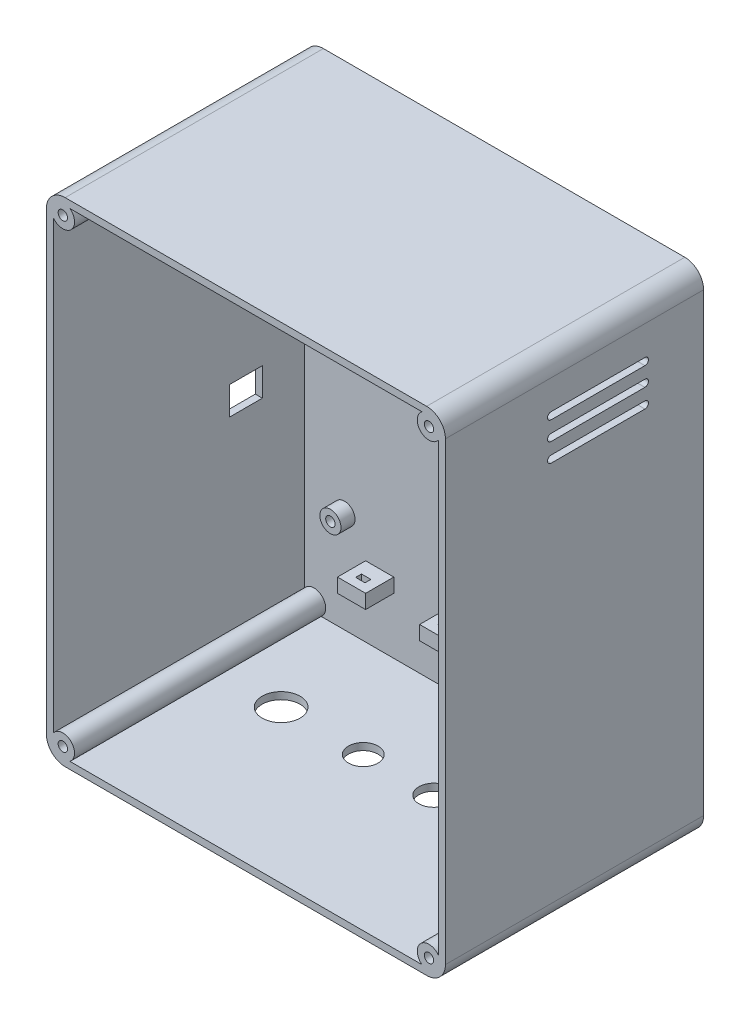
SolidWorks part; units mm, degrees
ref_plane "Front Plane" through (0, 0, 0) normal (0, 0, 1) x (1, 0, 0)
ref_plane "Top Plane" through (0, 0, 0) normal (0, 1, 0) x (1, 0, 0)
ref_plane "Right Plane" through (0, 0, 0) normal (1, 0, 0) x (0, 0, -1)
sketch "Sketch1" plane through (0, 0, 0) normal (0, 0, 1) x (1, 0, 0)
  line L0 (-77, 0) -> (77, 0)
  line L1 (85, 8) -> (85, 202)
  line L2 (77, 210) -> (-77, 210)
  line L3 (-85, 202) -> (-85, 8)
  arc A0 (-85, 8) -> (-77, 0) centre (-77, 8) ccw
  arc A1 (77, 0) -> (85, 8) centre (77, 8) ccw
  arc A2 (85, 202) -> (77, 210) centre (77, 202) ccw
  arc A3 (-77, 210) -> (-85, 202) centre (-77, 202) ccw
extrude "Block" add sketch "Sketch1" along normal blind 110
shell "Shell1" thickness 3
sketch "Sketch2" plane through (0, 0, 0) normal (0, 0, 1) x (1, 0, 0)
  circle A0 centre (-78, 7) radius 5
  circle A1 centre (78, 7) radius 5
  circle A2 centre (-78, 203) radius 5
  circle A3 centre (78, 203) radius 5
extrude "Corner columns" add sketch "Sketch2" along normal blind 110
ref_plane "P1_Front_110" through (0, 0, 110) normal (0, 0, 1) x (1, 0, 0)
sketch "Sketch3" plane through (0, 0, 110) normal (0, 0, 1) x (1, 0, 0)
  circle A0 centre (-78, 7) radius 2
  circle A1 centre (78, 7) radius 2
  circle A2 centre (-78, 203) radius 2
  circle A3 centre (78, 203) radius 2
extrude "Front panel insert holes" cut sketch "Sketch3" against normal blind 7
ref_plane "P2_Front_3" through (0, 0, 3) normal (0, 0, 1) x (1, 0, 0)
sketch "Sketch4" plane through (0, 0, 3) normal (0, 0, 1) x (1, 0, 0)
  circle A0 centre (-65, 46) radius 4.5
  circle A1 centre (65, 46) radius 4.5
  circle A2 centre (-65, 190) radius 4.5
  circle A3 centre (65, 190) radius 4.5
extrude "Plate bosses" add sketch "Sketch4" along normal blind 6
ref_plane "P3_Front_9" through (0, 0, 9) normal (0, 0, 1) x (1, 0, 0)
sketch "Sketch5" plane through (0, 0, 9) normal (0, 0, 1) x (1, 0, 0)
  circle A0 centre (-65, 46) radius 2
  circle A1 centre (65, 46) radius 2
  circle A2 centre (-65, 190) radius 2
  circle A3 centre (65, 190) radius 2
extrude "Plate insert holes" cut sketch "Sketch5" against normal blind 7
sketch "Sketch6" plane through (0, 0, 0) normal (0, 1, 0) x (1, 0, 0)
  circle A0 centre (-50, -45) radius 8.1
  circle A1 centre (-15, -45) radius 6.3
  circle A2 centre (15, -45) radius 6.3
  circle A3 centre (50, -45) radius 6.3
extrude "Cable gland holes" cut sketch "Sketch6" along normal blind 4
sketch "Sketch7" plane through (0, 0, 3) normal (0, 0, 1) x (1, 0, 0)
  line L1 (-56, 27) -> (-44, 27)
  line L2 (-56, 27) -> (-56, 33)
  line L3 (-56, 33) -> (-44, 33)
  line L4 (-44, 27) -> (-44, 33)
  line L5 (-56, 27) -> (-44, 33) construction
  line L6 (-56, 33) -> (-44, 27) construction
  line L7 (-21, 27) -> (-9, 27)
  line L8 (-21, 27) -> (-21, 33)
  line L9 (-21, 33) -> (-9, 33)
  line L10 (-9, 27) -> (-9, 33)
  line L11 (-21, 27) -> (-9, 33) construction
  line L12 (-21, 33) -> (-9, 27) construction
  line L13 (9, 27) -> (21, 27)
  line L14 (9, 27) -> (9, 33)
  line L15 (9, 33) -> (21, 33)
  line L16 (21, 27) -> (21, 33)
  line L17 (9, 27) -> (21, 33) construction
  line L18 (9, 33) -> (21, 27) construction
  line L19 (44, 27) -> (56, 27)
  line L20 (44, 27) -> (44, 33)
  line L21 (44, 33) -> (56, 33)
  line L22 (56, 27) -> (56, 33)
  line L23 (44, 27) -> (56, 33) construction
  line L24 (44, 33) -> (56, 27) construction
  point P0 (-50, 30)
  point P5 (-15, 30)
  point P10 (15, 30)
  point P15 (50, 30)
extrude "Cable tie bars" add sketch "Sketch7" along normal blind 12
ref_plane "P4_Top_26.99" through (0, 26.99, 0) normal (0, 1, 0) x (1, 0, 0)
sketch "Sketch8" plane through (0, 26.99, 0) normal (0, 1, 0) x (1, 0, 0)
  line L1 (-52, -11.25) -> (-48, -11.25)
  line L2 (-52, -11.25) -> (-52, -8.75)
  line L3 (-52, -8.75) -> (-48, -8.75)
  line L4 (-48, -11.25) -> (-48, -8.75)
  line L5 (-52, -11.25) -> (-48, -8.75) construction
  line L6 (-52, -8.75) -> (-48, -11.25) construction
  line L7 (-17, -11.25) -> (-13, -11.25)
  line L8 (-17, -11.25) -> (-17, -8.75)
  line L9 (-17, -8.75) -> (-13, -8.75)
  line L10 (-13, -11.25) -> (-13, -8.75)
  line L11 (-17, -11.25) -> (-13, -8.75) construction
  line L12 (-17, -8.75) -> (-13, -11.25) construction
  line L13 (13, -11.25) -> (17, -11.25)
  line L14 (13, -11.25) -> (13, -8.75)
  line L15 (13, -8.75) -> (17, -8.75)
  line L16 (17, -11.25) -> (17, -8.75)
  line L17 (13, -11.25) -> (17, -8.75) construction
  line L18 (13, -8.75) -> (17, -11.25) construction
  line L19 (48, -11.25) -> (52, -11.25)
  line L20 (48, -11.25) -> (48, -8.75)
  line L21 (48, -8.75) -> (52, -8.75)
  line L22 (52, -11.25) -> (52, -8.75)
  line L23 (48, -11.25) -> (52, -8.75) construction
  line L24 (48, -8.75) -> (52, -11.25) construction
  point P0 (-50, -10)
  point P5 (-15, -10)
  point P10 (15, -10)
  point P15 (50, -10)
extrude "Cable tie slots" cut sketch "Sketch8" along normal blind 6.02
ref_plane "P5_Right_-85" through (-85, 0, 0) normal (1, 0, 0) x (0, 0, -1)
sketch "Sketch9" plane through (-85, 0, 0) normal (1, 0, 0) x (0, 0, -1)
  line L1 (-35, 89) -> (-21, 89)
  line L2 (-35, 89) -> (-35, 101)
  line L3 (-35, 101) -> (-21, 101)
  line L4 (-21, 89) -> (-21, 101)
  line L5 (-35, 89) -> (-21, 101) construction
  line L6 (-35, 101) -> (-21, 89) construction
  point P0 (-28, 95)
extrude "USB access" cut sketch "Sketch9" along normal blind 4
ref_plane "P6_Right_-85" through (-85, 0, 0) normal (1, 0, 0) x (0, 0, -1)
sketch "Sketch10" plane through (-85, 0, 0) normal (1, 0, 0) x (0, 0, -1)
  line L0 (-25, 172) -> (-65, 172) construction
  line L1 (-25, 170.5) -> (-65, 170.5)
  line L2 (-25, 173.5) -> (-65, 173.5)
  line L3 (-25, 180) -> (-65, 180) construction
  line L4 (-25, 178.5) -> (-65, 178.5)
  line L5 (-25, 181.5) -> (-65, 181.5)
  line L6 (-25, 188) -> (-65, 188) construction
  line L7 (-25, 186.5) -> (-65, 186.5)
  line L8 (-25, 189.5) -> (-65, 189.5)
  arc A0 (-25, 170.5) -> (-25, 173.5) centre (-25, 172) ccw
  arc A1 (-65, 173.5) -> (-65, 170.5) centre (-65, 172) ccw
  arc A2 (-25, 178.5) -> (-25, 181.5) centre (-25, 180) ccw
  arc A3 (-65, 181.5) -> (-65, 178.5) centre (-65, 180) ccw
  arc A4 (-25, 186.5) -> (-25, 189.5) centre (-25, 188) ccw
  arc A5 (-65, 189.5) -> (-65, 186.5) centre (-65, 188) ccw
  point P2 (-45, 172)
  point P7 (-45, 180)
  point P14 (-45, 188)
extrude "Vents left" cut sketch "Sketch10" along normal blind 4
ref_plane "P7_Right_85" through (85, 0, 0) normal (1, 0, 0) x (0, 0, -1)
sketch "Sketch11" plane through (85, 0, 0) normal (1, 0, 0) x (0, 0, -1)
  line L0 (-25, 172) -> (-65, 172) construction
  line L1 (-25, 170.5) -> (-65, 170.5)
  line L2 (-25, 173.5) -> (-65, 173.5)
  line L3 (-25, 180) -> (-65, 180) construction
  line L4 (-25, 178.5) -> (-65, 178.5)
  line L5 (-25, 181.5) -> (-65, 181.5)
  line L6 (-25, 188) -> (-65, 188) construction
  line L7 (-25, 186.5) -> (-65, 186.5)
  line L8 (-25, 189.5) -> (-65, 189.5)
  arc A0 (-25, 170.5) -> (-25, 173.5) centre (-25, 172) ccw
  arc A1 (-65, 173.5) -> (-65, 170.5) centre (-65, 172) ccw
  arc A2 (-25, 178.5) -> (-25, 181.5) centre (-25, 180) ccw
  arc A3 (-65, 181.5) -> (-65, 178.5) centre (-65, 180) ccw
  arc A4 (-25, 186.5) -> (-25, 189.5) centre (-25, 188) ccw
  arc A5 (-65, 189.5) -> (-65, 186.5) centre (-65, 188) ccw
  point P2 (-45, 172)
  point P7 (-45, 180)
  point P14 (-45, 188)
extrude "Vents right" cut sketch "Sketch11" against normal blind 4
sketch "Sketch12" plane through (0, 0, 0) normal (0, 0, 1) x (1, 0, 0)
  circle A0 centre (-45, 165) radius 4.75
  circle A1 centre (45, 165) radius 4.75
extrude "Keyhole heads" cut sketch "Sketch12" along normal blind 4
sketch "Sketch13" plane through (0, 0, 0) normal (0, 0, 1) x (1, 0, 0)
  line L0 (-45, 165) -> (-45, 176) construction
  line L1 (-47.4, 165) -> (-47.4, 176)
  line L2 (-42.6, 165) -> (-42.6, 176)
  line L3 (45, 165) -> (45, 176) construction
  line L4 (42.6, 165) -> (42.6, 176)
  line L5 (47.4, 165) -> (47.4, 176)
  arc A0 (-47.4, 165) -> (-42.6, 165) centre (-45, 165) ccw
  arc A1 (-42.6, 176) -> (-47.4, 176) centre (-45, 176) ccw
  arc A2 (42.6, 165) -> (47.4, 165) centre (45, 165) ccw
  arc A3 (47.4, 176) -> (42.6, 176) centre (45, 176) ccw
  point P2 (-45, 170.5)
  point P7 (45, 170.5)
extrude "Keyhole slots" cut sketch "Sketch13" along normal blind 4
